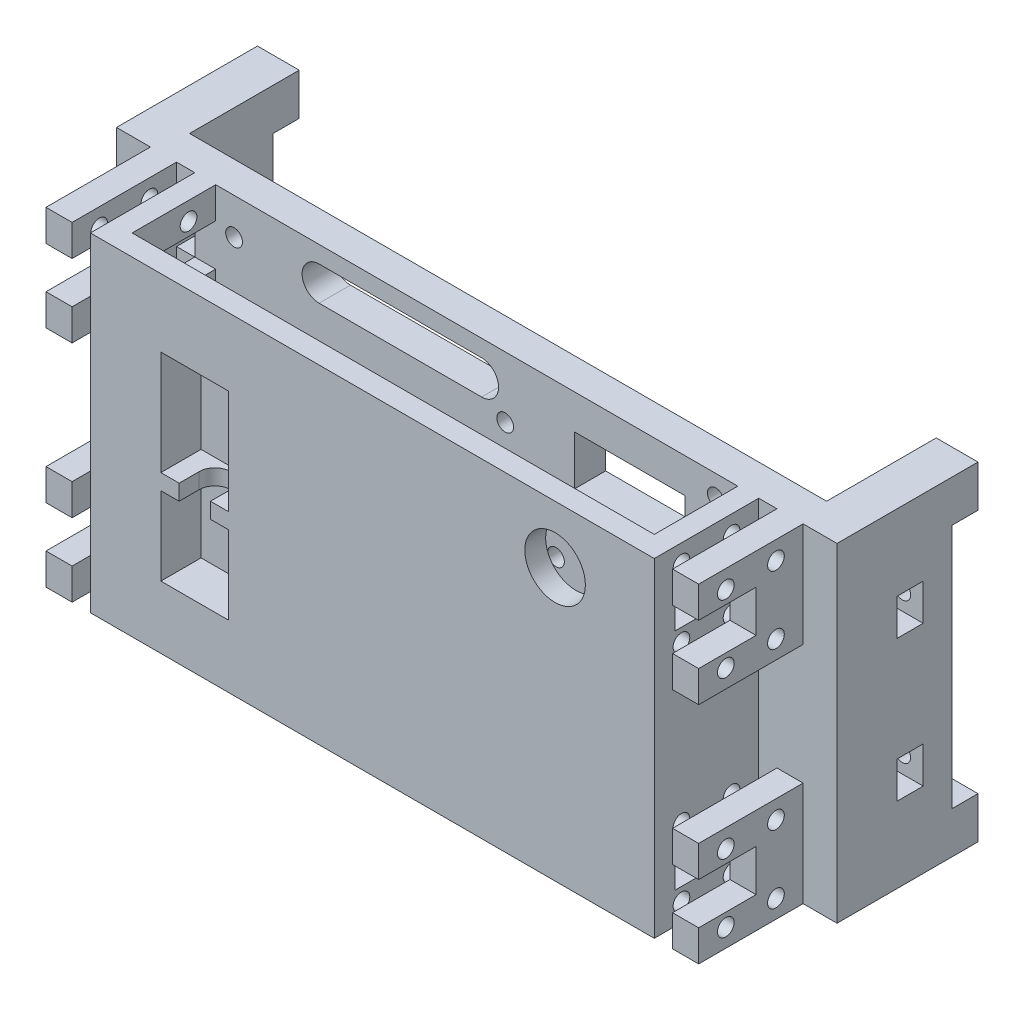
SolidWorks part; units mm, degrees
ref_plane "Plano frontal" through (0, 0, 0) normal (0, 0, 1) x (1, 0, 0)
ref_plane "Plano superior" through (0, 0, 0) normal (0, 1, 0) x (1, 0, 0)
ref_plane "Plano direito" through (0, 0, 0) normal (1, 0, 0) x (0, 0, -1)
sketch "Esboço1" plane through (0, 0, 0) normal (0, 0, 1) x (1, 0, 0)
  line L0 (0, -31.682) -> (0, -0.182)
  line L1 (0, -31.682) -> (-69, -31.682)
  line L3 (0, -0.182) -> (-69, -0.182)
  line L4 (-69, -31.682) -> (-69, -0.182)
  point P0 (0, 0)
  dimension "D1" = 31.5
  dimension "D2" = 69
extrude "Ressalto-extrusão1" add sketch "Esboço1" along normal blind 6
sketch "Esboço2" plane through (0, 0, 6) normal (0, 0, 1) x (1, 0, 0)
  line L0 (-69, -31.682) -> (0, -31.682) construction
  line L1 (-62.5, -31.682) -> (-57.5, -31.682)
  line L2 (-62.5, -31.682) -> (-62.5, -11.682)
  line L3 (-62.5, -11.682) -> (-57.5, -11.682)
  line L4 (-57.5, -31.682) -> (-57.5, -11.682)
  line L5 (-69, -0.182) -> (-69, -31.682) construction
  dimension "D1" = 20
  dimension "D2" = 5
  dimension "D3" = 6.5
extrude "Ressalto-extrusão2" add sketch "Esboço2" along normal blind 20
sketch "Esboço3" plane through (0, 0, 26) normal (0, 0, 1) x (1, 0, 0)
  line L0 (-57.5, -31.682) -> (-57.5, -11.682) construction
  line L1 (-57.5, -17.682) -> (-62.5, -17.682)
  line L2 (-57.5, -17.682) -> (-57.5, -25.682)
  line L3 (-57.5, -25.682) -> (-62.5, -25.682)
  line L4 (-62.5, -17.682) -> (-62.5, -25.682)
  line L5 (-62.5, -11.682) -> (-62.5, -31.682) construction
  line L6 (-57.5, -11.682) -> (-62.5, -11.682) construction
  line L7 (-62.5, -31.682) -> (-57.5, -31.682) construction
  dimension "D1" = 6
  dimension "D2" = 6
extrude "Corte-extrusão1" cut sketch "Esboço3" against normal blind 11
sketch "Esboço4" plane through (0, 0, 6) normal (0, 0, 1) x (1, 0, 0)
  line L0 (-57.5, -31.682) -> (0, -31.682) construction
  line L1 (-54, -31.682) -> (-50, -31.682)
  line L2 (-54, -31.682) -> (-54, -0.182)
  line L3 (-54, -0.182) -> (-50, -0.182)
  line L4 (-50, -31.682) -> (-50, -0.182)
  line L5 (0, -0.182) -> (-69, -0.182) construction
  line L6 (-57.5, -31.682) -> (-57.5, -11.682) construction
  dimension "D1" = 3.5
  dimension "D2" = 4
extrude "Ressalto-extrusão3" add sketch "Esboço4" along normal blind 20
sketch "Esboço5" plane through (-50, 0, 0) normal (1, 0, 0) x (0, 0, -1)
  line L0 (-15, -25.682) -> (-6, -25.682)
  line L2 (-22, -17.682) -> (-22, -6.182)
  line L5 (-15, -17.682) -> (-6, -17.682)
  line L6 (-22, -6.182) -> (-22, -0.182)
  line L7 (-26, -0.182) -> (-6, -0.182) construction
  line L10 (-26, -31.682) -> (-26, -0.182) construction
  line L11 (-22, -17.682) -> (-22, -25.682)
  line L12 (-6, -31.682) -> (-6, -0.182) construction
  line L13 (-6, -25.682) -> (-6, -17.682)
  line L20 (-15, -17.682) -> (-15, -25.682)
  line L21 (-15, -25.682) -> (-26, -25.682)
  line L22 (-26, -25.682) -> (-26, -31.682)
  line L23 (-26, -31.682) -> (-6, -31.682)
  line L24 (-6, -31.682) -> (-6, -11.682)
  line L25 (-6, -11.682) -> (-26, -11.682)
  line L26 (-26, -11.682) -> (-26, -17.682)
  line L27 (-26, -17.682) -> (-15, -17.682)
  line L29 (-15, -25.682) -> (-22, -25.682)
  line L32 (-6, -25.682) -> (-6, -17.682)
  line L35 (-22, -17.682) -> (-15, -17.682)
  line M8 (-6, -31.682) -> (-6, -0.182)
  dimension "D1" = 4
  dimension "D2" = 0
extrude "Corte-extrusão2" cut sketch "Esboço5" against normal up to surface (4 mm away) contours L35 L11 L29 L0 L5 M8
sketch "Esboço31" plane through (0, 0, 6) normal (0, 0, 1) x (1, 0, 0)
  line L0 (-57.5, -25.682) -> (-57.5, -17.682) construction
  line L1 (-57.5, -25.682) -> (-57.5, -17.682)
  line L3 (-54, -25.682) -> (-57.5, -25.682)
  line L4 (-54, -25.682) -> (-54, -17.682)
  line L5 (-54, -17.682) -> (-57.5, -17.682)
  line L6 (-57.5, -25.682) -> (-57.5, -17.682)
  line M10 (-57.5, -11.682) -> (-57.5, -31.682)
extrude "Corte-extrusão14" cut sketch "Esboço31" against normal up to surface (6 mm away) contours L4 L5 L3 M10 up to face at (-34.5, -15.932, 0)
sketch "Esboço38" plane through (-62.5, 0, 0) normal (-1, 0, 0) x (0, 0, 1)
  line L0 (26, -31.682) -> (6, -31.682) construction
  line L1 (20.8, -15.182) -> (11.2, -15.182) construction
  line L2 (20.8, -15.182) -> (20.8, -28.182) construction
  line L3 (20.8, -28.182) -> (11.2, -28.182) construction
  line L4 (11.2, -15.182) -> (11.2, -28.182) construction
  line L5 (16, -28.182) -> (16, -15.182) construction
  line L6 (20.8, -21.682) -> (11.2, -21.682) construction
  line L7 (26, -11.682) -> (6, -11.682) construction
  line L8 (6, -11.682) -> (6, -31.682) construction
  line L9 (26, -0.182) -> (26, -31.682) construction
  circle A0 centre (11.2, -15.182) radius 1.6
  circle A1 centre (20.8, -15.182) radius 1.6
  circle A2 centre (20.8, -28.182) radius 1.6
  circle A3 centre (11.2, -28.182) radius 1.6
  point P300 (16, -21.682)
  dimension "D1" = 3.2
  dimension "D2" = 3.5
  dimension "D3" = 3.5
  dimension "D4" = 5.2
  dimension "D5" = 5.2
extrude "Corte-extrusão19" cut sketch "Esboço38" against normal up to surface (12.5 mm away)
sketch "Esboço6" plane through (-50, 0, 0) normal (1, 0, 0) x (0, 0, -1)
  line L0 (-26, -31.682) -> (-26, -0.182) construction
  line L1 (-26, -31.682) -> (-22, -31.682)
  line L2 (-26, -31.682) -> (-26, -0.182)
  line L5 (-22, -31.682) -> (-22, -0.182)
  line L6 (-26, -0.182) -> (-6, -0.182) construction
  line L7 (-22, -0.182) -> (-26, -0.182)
  line L8 (-22, -17.682) -> (-22, -25.682) construction
extrude "Ressalto-extrusão4" add sketch "Esboço6" along normal up to surface (50 mm away) up to face at (0, -15.932, 3)
ref_plane "Plano2" through (0, -0.182, 0) normal (0, 1, 0) x (1, 0, 0)
mirror "Espelhar10" about plane through (0, -0.182, 0) normal (0, 1, 0) of bodies 110 103
ref_plane "Plano1" through (0, 0, 0) normal (1, 0, 0) x (0, 0, -1)
mirror "Espelhar11" about plane through (0, 0, 0) normal (1, 0, 0) of bodies 106
sketch "Esboço18" plane through (-54, 0, 0) normal (-1, 0, 0) x (0, 0, 1)
  line L0 (6, -31.682) -> (26, 31.318) construction
  line L1 (6, 31.318) -> (26, -31.682) construction
  line L12 (6, -17.682) -> (22, -17.682)
  line L13 (22, -17.682) -> (22, -25.682)
  line L14 (22, -25.682) -> (6, -25.682)
  line L15 (6, -25.682) -> (6, -31.682)
  line L16 (6, -31.682) -> (26, -31.682)
  line L17 (26, -31.682) -> (26, 31.318)
  line L18 (26, 31.318) -> (6, 31.318)
  line L19 (6, 31.318) -> (6, 25.318)
  line L20 (6, 25.318) -> (22, 25.318)
  line L21 (22, 25.318) -> (22, 17.318)
  line L22 (22, 17.318) -> (6, 17.318)
  line L23 (6, 17.318) -> (6, -17.682)
  line L24 (6, -17.682) -> (22, -17.682)
  line L25 (22, -17.682) -> (22, -25.682)
  line L26 (22, -25.682) -> (6, -25.682)
  line L28 (6, -31.682) -> (26, -31.682)
  line L29 (26, -31.682) -> (26, 31.318)
  line L30 (26, 31.318) -> (6, 31.318)
  line L31 (6, 31.318) -> (6, 25.318)
  line L32 (6, 25.318) -> (22, 25.318)
  line L33 (22, 25.318) -> (22, 17.318)
  line L34 (22, 17.318) -> (6, 17.318)
  line L35 (6, 17.318) -> (6, -17.682)
  line L38 (6, -25.682) -> (6, -31.682)
  circle A0 centre (16, -0.182) radius 3.8
  dimension "D2" = 7.6
  dimension "D1" = 0
extrude "Corte-extrusão3" cut sketch "Esboço18" against normal up to surface (4 mm away) contours A0 up to face at (-50, 27.818, 12.8)
sketch "Esboço19" plane through (0, 0, 26) normal (0, 0, 1) x (1, 0, 0)
  line L0 (20, -65.2403) -> (50, -65.2403)
  line L7 (50, -65.2403) -> (20, -65.2403)
  line L8 (50, -65.2403) -> (50, 31.318)
  line L9 (50, 31.318) -> (20, 31.318)
  line L10 (20, -65.2403) -> (20, 31.318)
  line L11 (35, -65.2403) -> (35, 31.318) construction
  line L13 (20, 20.318) -> (50, 20.318) construction
  line L20 (-54, -17.682) -> (-54, -25.682)
  line L21 (-50, -17.682) -> (-54, -17.682)
  line L22 (-50, -16.2403) -> (-50, -17.682)
  line L23 (-54, 17.318) -> (-50, 17.318)
  line L24 (-54, 25.318) -> (-54, 17.318)
  line L25 (-50, 25.318) -> (-54, 25.318)
  line L26 (-50, 26.7597) -> (-50, 25.318)
  line L27 (50, 31.318) -> (-50, 31.318)
  line L28 (50, 28.8763) -> (50, 31.318)
  line L29 (54, 25.318) -> (50, 25.318)
  line L30 (54, 17.318) -> (54, 25.318)
  line L31 (50, 17.318) -> (54, 17.318)
  line L32 (50, 15.8763) -> (50, 17.318)
  line L33 (54, -17.682) -> (50, -17.682)
  line L34 (54, -25.682) -> (54, -17.682)
  line L35 (50, -25.682) -> (54, -25.682)
  line L36 (50, -27.1237) -> (50, -25.682)
  line L37 (-50, -31.682) -> (50, -31.682)
  line L38 (-50, -29.2403) -> (-50, -31.682)
  line L39 (-54, -25.682) -> (-50, -25.682)
  line L47 (50, 31.318) -> (-50, 31.318)
  line L48 (50, 28.8763) -> (50, 31.318)
  line L49 (54, 25.318) -> (50, 25.318)
  line L50 (54, 17.318) -> (54, 25.318)
  line L51 (50, 17.318) -> (54, 17.318)
  line L52 (50, 15.8763) -> (50, 17.318)
  line L53 (54, -17.682) -> (50, -17.682)
  line L54 (54, -25.682) -> (54, -17.682)
  line L55 (50, -25.682) -> (54, -25.682)
  line L56 (50, -27.1237) -> (50, -25.682)
  line L57 (-50, -31.682) -> (50, -31.682)
  line L85 (-50, -14.1237) -> (-50, -16.2403)
  line L86 (-50, -14.1237) -> (-50, -16.2403)
  line L87 (-50, 13.7597) -> (-50, -14.1237)
  line L88 (-50, 13.7597) -> (-50, -14.1237)
  line L89 (-50, 15.8763) -> (-50, 13.7597)
  line L90 (-50, 15.8763) -> (-50, 13.7597)
  line L91 (-50, 17.318) -> (-50, 15.8763)
  line L92 (-50, 17.318) -> (-50, 15.8763)
  line L93 (-50, 28.8763) -> (-50, 26.7597)
  line L94 (-50, 28.8763) -> (-50, 26.7597)
  line L95 (-50, 31.318) -> (-50, 28.8763)
  line L96 (-50, 31.318) -> (-50, 28.8763)
  line L97 (50, 26.7597) -> (50, 28.8763)
  line L98 (50, 26.7597) -> (50, 28.8763)
  line L99 (50, 25.318) -> (50, 26.7597)
  line L100 (50, 25.318) -> (50, 26.7597)
  line L101 (50, 13.7597) -> (50, 15.8763)
  line L102 (50, 13.7597) -> (50, 15.8763)
  line L103 (50, -14.1237) -> (50, 13.7597)
  line L104 (50, -14.1237) -> (50, 13.7597)
  line L105 (50, -16.2403) -> (50, -14.1237)
  line L106 (50, -16.2403) -> (50, -14.1237)
  line L107 (50, -17.682) -> (50, -16.2403)
  line L108 (50, -17.682) -> (50, -16.2403)
  line L109 (50, -29.2403) -> (50, -27.1237)
  line L110 (50, -29.2403) -> (50, -27.1237)
  line L111 (50, -31.682) -> (50, -29.2403)
  line L112 (50, -31.682) -> (50, -29.2403)
  line L113 (-50, -27.1237) -> (-50, -29.2403)
  line L114 (-50, -27.1237) -> (-50, -29.2403)
  line L115 (-50, -25.682) -> (-50, -27.1237)
  line L116 (-50, -25.682) -> (-50, -27.1237)
  circle A1 centre (35, 20.318) radius 5.8
  dimension "D7" = 11.6
  dimension "D5" = 30
  dimension "D6" = 11
  dimension "D1" = 0
extrude "Corte-extrusão5" cut sketch "Esboço19" against normal up to surface (4 mm away) contours A1
sketch "Esboço20" plane through (0, 0, 22) normal (0, 0, -1) x (-1, 0, 0)
  line L0 (34, 22.318) -> (34, 31.318) construction
  line L5 (24, 22.318) -> (44, 22.318)
  line L6 (24, 22.318) -> (24, -22.682)
  line L7 (24, -22.682) -> (44, -22.682)
  line L8 (44, 22.318) -> (44, -22.682)
  line L10 (34, -22.682) -> (34, -31.682) construction
  line L20 (54, -25.682) -> (54, -17.682)
  line L21 (54, -17.682) -> (50, -17.682)
  line L22 (50, -17.682) -> (50, -16.2403)
  line L23 (50, 17.318) -> (54, 17.318)
  line L24 (54, 17.318) -> (54, 25.318)
  line L25 (54, 25.318) -> (50, 25.318)
  line L26 (50, 25.318) -> (50, 26.7597)
  line L27 (50, 31.318) -> (-50, 31.318)
  line L28 (-50, 31.318) -> (-50, 28.8763)
  line L29 (-50, 25.318) -> (-54, 25.318)
  line L30 (-54, 25.318) -> (-54, 17.318)
  line L31 (-54, 17.318) -> (-50, 17.318)
  line L32 (-50, 17.318) -> (-50, 15.8763)
  line L33 (-50, -17.682) -> (-54, -17.682)
  line L34 (-54, -17.682) -> (-54, -25.682)
  line L35 (-54, -25.682) -> (-50, -25.682)
  line L36 (-50, -25.682) -> (-50, -27.1237)
  line L37 (-50, -31.682) -> (50, -31.682)
  line L38 (50, -31.682) -> (50, -29.2403)
  line L39 (50, -25.682) -> (54, -25.682)
  line L40 (54, -25.682) -> (54, -17.682)
  line L41 (54, -17.682) -> (50, -17.682)
  line L42 (50, -17.682) -> (50, -16.2403)
  line L43 (50, 17.318) -> (54, 17.318)
  line L44 (54, 17.318) -> (54, 25.318)
  line L45 (54, 25.318) -> (50, 25.318)
  line L46 (50, 25.318) -> (50, 26.7597)
  line L47 (50, 31.318) -> (-50, 31.318)
  line L48 (-50, 31.318) -> (-50, 28.8763)
  line L49 (-50, 25.318) -> (-54, 25.318)
  line L50 (-54, 25.318) -> (-54, 17.318)
  line L51 (-54, 17.318) -> (-50, 17.318)
  line L52 (-50, 17.318) -> (-50, 15.8763)
  line L53 (-50, -17.682) -> (-54, -17.682)
  line L54 (-54, -17.682) -> (-54, -25.682)
  line L55 (-54, -25.682) -> (-50, -25.682)
  line L56 (-50, -25.682) -> (-50, -27.1237)
  line L57 (-50, -31.682) -> (50, -31.682)
  line L58 (50, -31.682) -> (50, -29.2403)
  line L59 (50, -25.682) -> (54, -25.682)
  line L86 (50, -16.2403) -> (50, -14.1237)
  line L87 (50, -16.2403) -> (50, -14.1237)
  line L88 (50, -14.1237) -> (50, 13.7597)
  line L89 (50, -14.1237) -> (50, 13.7597)
  line L90 (50, 13.7597) -> (50, 15.8763)
  line L91 (50, 13.7597) -> (50, 15.8763)
  line L92 (50, 15.8763) -> (50, 17.318)
  line L93 (50, 15.8763) -> (50, 17.318)
  line L94 (50, 26.7597) -> (50, 28.8763)
  line L95 (50, 26.7597) -> (50, 28.8763)
  line L96 (50, 28.8763) -> (50, 31.318)
  line L97 (50, 28.8763) -> (50, 31.318)
  line L98 (-50, 28.8763) -> (-50, 26.7597)
  line L99 (-50, 28.8763) -> (-50, 26.7597)
  line L100 (-50, 26.7597) -> (-50, 25.318)
  line L101 (-50, 26.7597) -> (-50, 25.318)
  line L102 (-50, 15.8763) -> (-50, 13.7597)
  line L103 (-50, 15.8763) -> (-50, 13.7597)
  line L104 (-50, 13.7597) -> (-50, -14.1237)
  line L105 (-50, 13.7597) -> (-50, -14.1237)
  line L106 (-50, -14.1237) -> (-50, -16.2403)
  line L107 (-50, -14.1237) -> (-50, -16.2403)
  line L108 (-50, -16.2403) -> (-50, -17.682)
  line L109 (-50, -16.2403) -> (-50, -17.682)
  line L110 (-50, -27.1237) -> (-50, -29.2403)
  line L111 (-50, -27.1237) -> (-50, -29.2403)
  line L112 (-50, -29.2403) -> (-50, -31.682)
  line L113 (-50, -29.2403) -> (-50, -31.682)
  line L114 (50, -29.2403) -> (50, -27.1237)
  line L115 (50, -29.2403) -> (50, -27.1237)
  line L116 (50, -27.1237) -> (50, -25.682)
  line L117 (50, -27.1237) -> (50, -25.682)
  dimension "D2" = 45
  dimension "D3" = 20
  dimension "D4" = 6
  dimension "D1" = 0
extrude "Ressalto-extrusão9" add sketch "Esboço20" along normal blind 7 contours L8 L5 L6 L7
sketch "Esboço21" plane through (0, 0, 26) normal (0, 0, 1) x (1, 0, 0)
  line L0 (-40.5, -12.182) -> (-44, -12.182) construction
  line L1 (-40.5, -19.682) -> (-27.5, -19.682)
  line L2 (-40.5, -19.682) -> (-40.5, -4.682)
  line L3 (-40.5, -4.682) -> (-27.5, -4.682)
  line L4 (-44, 22.318) -> (-44, -22.682)
  line L5 (-24, 22.318) -> (-44, 22.318)
  line L6 (-24, -22.682) -> (-24, 22.318)
  line L7 (-44, -22.682) -> (-24, -22.682)
  line L8 (-44, 22.318) -> (-44, -22.682)
  line L9 (-24, 22.318) -> (-44, 22.318)
  line L10 (-24, -22.682) -> (-24, 22.318)
  line L11 (-44, -22.682) -> (-24, -22.682)
  line L12 (-27.5, -19.682) -> (-27.5, -4.682)
  line L13 (-24, -12.182) -> (-27.5, -12.182) construction
  dimension "D2" = 13
  dimension "D3" = 15
  dimension "D4" = 3
  dimension "D1" = 0
extrude "Corte-extrusão6" cut sketch "Esboço21" against normal blind 7.7 contours L2 L1 L12 L3
sketch "Esboço22" plane through (0, 0, 26) normal (0, 0, 1) x (1, 0, 0)
  line L0 (-40.5, -19.682) -> (-40.5, -4.682) construction
  line L1 (-40.5, -1.682) -> (-27.5, -1.682)
  line L2 (-40.5, -1.682) -> (-40.5, 18.318)
  line L3 (-40.5, 18.318) -> (-27.5, 18.318)
  line L4 (-44, 22.318) -> (-44, -22.682)
  line L5 (-24, 22.318) -> (-44, 22.318)
  line L6 (-24, -22.682) -> (-24, 22.318)
  line L7 (-44, -22.682) -> (-24, -22.682)
  line L8 (-44, 22.318) -> (-44, -22.682)
  line L9 (-24, 22.318) -> (-44, 22.318)
  line L10 (-24, -22.682) -> (-24, 22.318)
  line L11 (-44, -22.682) -> (-24, -22.682)
  line L12 (-27.5, -1.682) -> (-27.5, 18.318)
  line L17 (-27.5, -4.682) -> (-40.5, -4.682)
  line L18 (-40.5, -4.682) -> (-40.5, -19.682)
  line L19 (-40.5, -19.682) -> (-27.5, -19.682)
  line L20 (-27.5, -19.682) -> (-27.5, -4.682)
  line L21 (-27.5, -4.682) -> (-40.5, -4.682)
  line L22 (-40.5, -4.682) -> (-40.5, -19.682)
  line L23 (-40.5, -19.682) -> (-27.5, -19.682)
  line L24 (-27.5, -19.682) -> (-27.5, -4.682)
  dimension "D2" = 20
  dimension "D3" = 13
  dimension "D5" = 3
  dimension "D1" = 0
  dimension "D4" = 0
extrude "Corte-extrusão7" cut sketch "Esboço22" against normal blind 7.7 contours L2 L1 L12 L3
sketch "Esboço23" plane through (0, -1.682, 0) normal (0, 1, 0) x (1, 0, 0)
  line L0 (-27.5, -26) -> (-40.5, -18.3) construction
  line L1 (-40.5, -26) -> (-27.5, -18.3) construction
  line L2 (-31, -22.15) -> (-27.5, -22.15)
  line L3 (-37, -22.15) -> (-40.5, -22.15)
  line L4 (-40.5, -26) -> (-27.5, -26)
  line L5 (-27.5, -26) -> (-27.5, -18.3)
  line L6 (-27.5, -18.3) -> (-40.5, -18.3)
  line L7 (-40.5, -18.3) -> (-40.5, -26)
  line L8 (-40.5, -26) -> (-27.5, -26)
  line L9 (-27.5, -26) -> (-27.5, -18.3)
  line L10 (-27.5, -18.3) -> (-40.5, -18.3)
  line L11 (-40.5, -18.3) -> (-40.5, -26)
  line L12 (-31, -22.15) -> (-31, -26)
  line L13 (-37, -22.15) -> (-37, -26)
  arc A0 (-31, -22.15) -> (-37, -22.15) centre (-34, -22.15) ccw
  dimension "D2" = 6
  dimension "D1" = 0
extrude "Corte-extrusão9" cut sketch "Esboço23" against normal up to surface (3 mm away) contours L12 A0 L13 L8 up to face at (-34, -4.682, 22.15)
sketch "Esboço24" plane through (0, 0, 0) normal (0, 0, -1) x (-1, 0, 0)
  line L0 (69, 31.318) -> (-69, 31.318) construction
  line L1 (69, -31.682) -> (61, -31.682)
  line L2 (69, -31.682) -> (69, 31.318)
  line L3 (69, 31.318) -> (61, 31.318)
  line L4 (61, -31.682) -> (61, 31.318)
  dimension "D1" = 8
extrude "Ressalto-extrusão10" add sketch "Esboço24" along normal blind 16
sketch "Esboço25" plane through (0, 0, 0) normal (0, 0, -1) x (-1, 0, 0)
  line L0 (61, 31.318) -> (-69, 31.318) construction
  line L1 (-69, -31.682) -> (-61, -31.682)
  line L2 (-69, -31.682) -> (-69, 31.318)
  line L3 (-69, 31.318) -> (-61, 31.318)
  line L4 (-61, -31.682) -> (-61, 31.318)
  dimension "D1" = 8
extrude "Ressalto-extrusão11" add sketch "Esboço25" along normal blind 16
sketch "Esboço27" plane through (-61, 0, 0) normal (1, 0, 0) x (0, 0, -1)
  line L1 (0, -16.882) -> (12.7, -16.882)
  line L2 (0, -16.882) -> (0, -4.482)
  line L3 (0, -4.482) -> (12.7, -4.482)
  line L4 (12.7, -16.882) -> (12.7, -4.482)
  line L6 (0, 31.318) -> (0, -31.682) construction
  line L7 (16, -31.682) -> (0, -31.682) construction
  dimension "D1" = 14.8
  dimension "D2" = 12.7
  dimension "D3" = 12.4
extrude "Corte-extrusão10" cut sketch "Esboço27" against normal through all
sketch "Esboço28" plane through (0, 0, 0) normal (0, 0, -1) x (-1, 0, 0)
  circle A0 centre (46.4832, 24.3566) radius 1.6
  circle A1 centre (-5.4471, 19.6068) radius 1.6
  circle A2 centre (-5.4471, -8.3205) radius 1.6
  circle A3 centre (45.3401, -23.5605) radius 1.6
  circle A4 centre (-15.175, -16.507) radius 1.6
  circle A5 centre (-15.175, 2.143) radius 1.6
  circle A6 centre (-15.5824, 11.068) radius 1.6
  circle A7 centre (-45.7824, 27.318) radius 1.6
  circle A8 centre (-42.5, 5.518) radius 1.6
  circle A9 centre (-26.25, -24.682) radius 1.6
  dimension "D1" = 3.2
extrude "Corte-extrusão11" cut sketch "Esboço28" against normal up to surface (6 mm away)
sketch "Esboço29" plane through (0, 0, 0) normal (0, 0, -1) x (-1, 0, 0)
  line L0 (36.9503, -24.432) -> (-15.7003, -24.432) construction
  line L1 (36.9503, -27.682) -> (-15.7003, -27.682)
  line L2 (36.9503, -21.182) -> (-15.7003, -21.182)
  line L3 (30.1987, 24.818) -> (-0.9316, 24.818) construction
  line L4 (30.1987, 21.568) -> (-0.9316, 21.568)
  line L5 (30.1987, 28.068) -> (-0.9316, 28.068)
  line L6 (61, -31.682) -> (-61, -31.682) construction
  line L7 (61, 31.318) -> (-61, 31.318) construction
  line L11 (44.4354, -12.415) -> (0, -12.415)
  line L14 (44.4354, -12.415) -> (44.4354, 14.2888)
  line L15 (44.4354, 14.2888) -> (0, 14.2888)
  line L16 (0, -12.415) -> (0, 14.2888)
  arc A0 (36.9503, -27.682) -> (36.9503, -21.182) centre (36.9503, -24.432) ccw
  arc A1 (-15.7003, -21.182) -> (-15.7003, -27.682) centre (-15.7003, -24.432) ccw
  arc A2 (30.1987, 21.568) -> (30.1987, 28.068) centre (30.1987, 24.818) ccw
  arc A3 (-0.9316, 28.068) -> (-0.9316, 21.568) centre (-0.9316, 24.818) ccw
  point P2 (10.625, -24.432)
  point P7 (14.6335, 24.818)
  dimension "D1" = 4
  dimension "D2" = 6.5
  dimension "D3" = 6.5
  dimension "D4" = 6.5
extrude "Corte-extrusão12" cut sketch "Esboço29" against normal up to surface (6 mm away) up to face at (44.1, 5.518, 6)
sketch "Esboço30" plane through (0, 0, 0) normal (0, 0, -1) x (-1, 0, 0)
  line L0 (-14.7856, -2.6598) -> (-14.7856, -12.7427)
  line L1 (-14.7856, -12.7427) -> (-20.8471, -12.7427)
  line L2 (-20.8471, -12.7427) -> (-20.8471, -12.7096)
  line L3 (-20.8471, -12.7096) -> (-43.5315, -12.7096)
  line L4 (-43.5315, -12.7096) -> (-43.5315, -2.6598)
  line L7 (-22.573, -2.6598) -> (-14.7856, -2.6598)
  line L8 (-18.6793, 15.184) -> (-18.6793, 24.6844)
  line L9 (-18.6793, 24.6844) -> (-39.8659, 24.6844)
  line L10 (-39.8659, 24.6844) -> (-39.8659, 15.184)
  line L11 (-39.8659, 15.184) -> (-18.6793, 15.184)
  line L12 (-22.573, -2.6598) -> (-43.5315, -2.6598)
extrude "Corte-extrusão13" cut sketch "Esboço30" against normal up to surface (6 mm away)
sketch "Esboço32" plane through (0, 0, -16) normal (0, 0, -1) x (-1, 0, 0)
  line L0 (69, -31.682) -> (69, 31.318) construction
  line L5 (-61, -31.682) -> (-61, 31.318) construction
  line L6 (61, 31.318) -> (69, 31.318)
  line L7 (61, 31.318) -> (61, 23.318)
  line L8 (61, 23.318) -> (69, 23.318)
  line L9 (69, 31.318) -> (69, 23.318)
  line L10 (-69, -31.682) -> (-61, -31.682)
  line L11 (-69, -31.682) -> (-69, -23.682)
  line L12 (-69, -23.682) -> (-61, -23.682)
  line L13 (-61, -31.682) -> (-61, -23.682)
  line L14 (61, 31.318) -> (61, -31.682) construction
  line L15 (-69, 31.318) -> (-61, 31.318)
  line L16 (-69, 31.318) -> (-69, 23.318)
  line L17 (-69, 23.318) -> (-61, 23.318)
  line L18 (-61, 31.318) -> (-61, 23.318)
  line L19 (69, -31.682) -> (61, -31.682)
  line L20 (69, -31.682) -> (69, -23.682)
  line L21 (69, -23.682) -> (61, -23.682)
  line L22 (61, -31.682) -> (61, -23.682)
  line L23 (65, -23.682) -> (65, -31.682) construction
  line L24 (69, -27.682) -> (61, -27.682) construction
  point P215 (65, -27.682)
  dimension "D2" = 8
extrude "Ressalto-extrusão12" add sketch "Esboço32" along normal blind 5
sketch "Esboço34" plane through (61, 0, 0) normal (-1, 0, 0) x (0, 0, 1)
  line L0 (-21, -31.682) -> (0, -31.682) construction
  line L1 (-16, -31.682) -> (0, -31.682) construction
  line L2 (-16, -31.682) -> (-16, 31.318) construction
  line L3 (-16, 31.318) -> (0, 31.318) construction
  line L4 (0, -31.682) -> (0, 31.318) construction
  line L5 (-16, -23.682) -> (-16, 23.318) construction
  line L6 (-8, -31.682) -> (-8, 31.318) construction
  line L7 (-10.5, -17.182) -> (-5.5, -17.182)
  line L8 (-10.5, -17.182) -> (-10.5, -10.182)
  line L9 (-10.5, -10.182) -> (-5.5, -10.182)
  line L10 (-5.5, -17.182) -> (-5.5, -10.182)
  line L11 (-8, -10.182) -> (-8, -17.182) construction
  line L12 (-10.5, -13.682) -> (-5.5, -13.682) construction
  line L13 (-10.5, 9.818) -> (-5.5, 9.818)
  line L14 (-10.5, 9.818) -> (-10.5, 16.818)
  line L15 (-10.5, 16.818) -> (-5.5, 16.818)
  line L16 (-5.5, 9.818) -> (-5.5, 16.818)
  line L17 (-8, 16.818) -> (-8, 9.818) construction
  line L18 (-10.5, 13.318) -> (-5.5, 13.318) construction
  line L19 (-16, -0.182) -> (0, -0.182)
  point P169 (-8, 13.318)
  point P210 (-8, -13.682)
  dimension "D1" = 20
  dimension "D2" = 5
  dimension "D3" = 7
  dimension "D4" = 10
extrude "Corte-extrusão15" cut sketch "Esboço34" against normal up to surface (8 mm away) contours L7 L10 L9 L8 | L13 L16 L15 L14 up to face at (69, -0.182, -13)
sketch "Esboço35" plane through (0, 0, -16) normal (0, 0, -1) x (-1, 0, 0)
  line L0 (-69, 16.818) -> (-61, 16.818) construction
  line L1 (-61, 16.818) -> (-61, 9.818) construction
  line L2 (-61, 9.818) -> (-69, 9.818) construction
  line L3 (-69, 9.818) -> (-69, 16.818) construction
  line L4 (-69, -10.182) -> (-61, -10.182) construction
  line L5 (-61, -10.182) -> (-61, -17.182) construction
  line L6 (-61, -17.182) -> (-69, -17.182) construction
  line L7 (-69, -17.182) -> (-69, -10.182) construction
  line L8 (-69, 16.818) -> (-61, 16.818)
  line L9 (-61, 16.818) -> (-61, 9.818)
  line L10 (-61, 9.818) -> (-69, 9.818)
  line L11 (-69, 9.818) -> (-69, 16.818)
  line L12 (-69, -10.182) -> (-61, -10.182)
  line L13 (-61, -10.182) -> (-61, -17.182)
  line L14 (-61, -17.182) -> (-69, -17.182)
  line L15 (-69, -17.182) -> (-69, -10.182)
  line L16 (-65, 16.818) -> (-65, 13.3172) construction
  line L17 (-65, 13.3172) -> (-65, 9.818) construction
  line L18 (-65, 9.818) -> (-65, -10.182) construction
  line L19 (-65, -10.182) -> (-65, -13.6844) construction
  line L20 (-65, -13.6844) -> (-65, -17.182) construction
  circle A0 centre (-65, -13.6844) radius 1.5869
  circle A1 centre (-65, 13.3172) radius 1.6
  dimension "D1" = 3.2
extrude "Corte-extrusão16" cut sketch "Esboço35" against normal up to surface (5.5 mm away) contours A1 | A0 up to face at (65, 13.318, -10.5)
sketch "Esboço36" plane through (-61, 0, 0) normal (1, 0, 0) x (0, 0, -1)
  line L1 (16, 23.318) -> (0, 23.318)
  line L2 (16, 23.318) -> (16, -4.482)
  line L3 (16, -4.482) -> (0, -4.482)
  line L4 (0, 23.318) -> (0, -4.482)
  line L5 (8, -4.482) -> (8, 23.318) construction
  line L6 (16, 9.418) -> (0, 9.418) construction
  line L7 (5.5, 5.918) -> (10.5, 5.918)
  line L8 (5.5, 5.918) -> (5.5, 12.918)
  line L9 (5.5, 12.918) -> (10.5, 12.918)
  line L10 (10.5, 5.918) -> (10.5, 12.918)
  line L11 (5.5, 5.918) -> (10.5, 12.918) construction
  line L12 (5.5, 12.918) -> (10.5, 5.918) construction
  point P4 (8, 9.418)
  point P272 (8, 9.418)
  dimension "D1" = 5
  dimension "D2" = 7
extrude "Corte-extrusão17" cut sketch "Esboço36" against normal up to surface (8 mm away) contours L10 L9 L8 L7 up to face at (-69, -10.682, -6.35)
sketch "Esboço37" plane through (0, 0, -16) normal (0, 0, -1) x (-1, 0, 0)
  line L0 (69, 12.918) -> (61, 5.918) construction
  line L1 (69, 5.918) -> (61, 12.918) construction
  line L4 (69, 12.918) -> (61, 12.918)
  line L5 (61, 12.918) -> (61, 5.918)
  line L6 (61, 5.918) -> (69, 5.918)
  line L7 (69, 5.918) -> (69, 12.918)
  line L8 (69, 12.918) -> (61, 12.918)
  line L9 (61, 12.918) -> (61, 5.918)
  line L10 (61, 5.918) -> (69, 5.918)
  line L11 (69, 5.918) -> (69, 12.918)
  circle A0 centre (65, 9.418) radius 1.6
  dimension "D2" = 3.2
  dimension "D1" = 0
extrude "Corte-extrusão18" cut sketch "Esboço37" against normal up to surface (10.5 mm away) contours A0 up to face at (-65, 9.418, -5.5)
